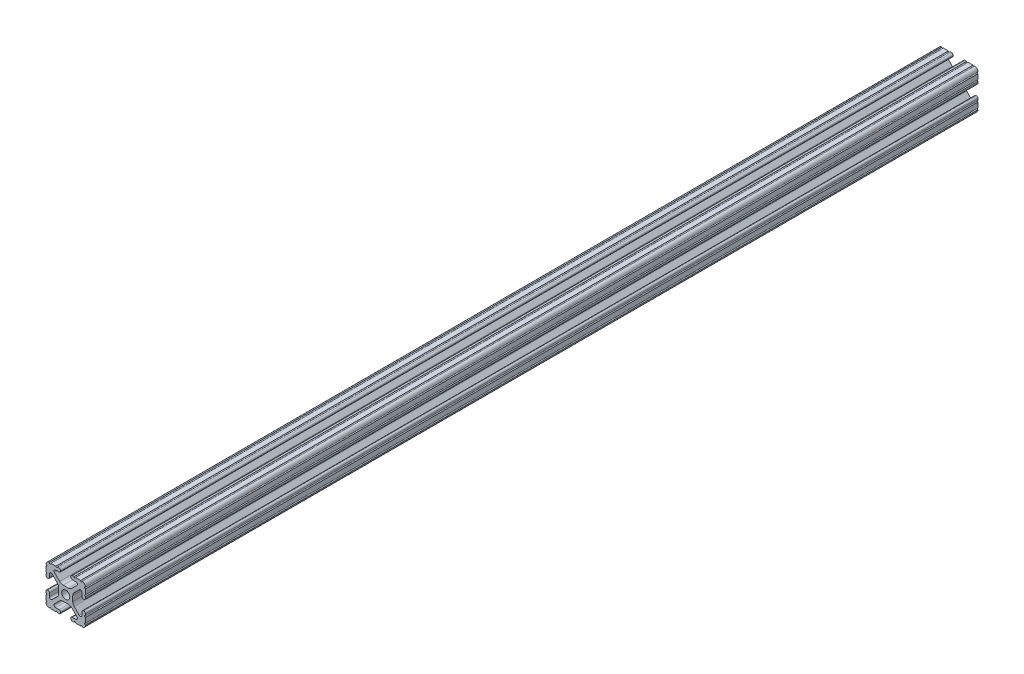
SolidWorks part; units mm, degrees
ref_plane "Front Plane" through (0, 0, 0) normal (0, 0, 1) x (1, 0, 0)
ref_plane "Top Plane" through (0, 0, 0) normal (0, 1, 0) x (1, 0, 0)
ref_plane "Right Plane" through (0, 0, 0) normal (1, 0, 0) x (0, 0, -1)
sketch "Sketch1" plane through (0, 0, 0) normal (0, 0, 1) x (1, 0, 0)
  line L88 (-7.1797, -8.6452) -> (-3.9523, -5.4237)
  line L89 (-1.7093, -4.4958) -> (1.7093, -4.4958)
  line L90 (3.9523, -5.4237) -> (7.1797, -8.6452)
  line L91 (6.4164, -10.4902) -> (4.2875, -10.4902)
  line L92 (3.2385, -11.5392) -> (3.2385, -11.651)
  line L93 (4.2875, -12.7) -> (5.3171, -12.7)
  line L94 (6.3331, -12.7) -> (9.5504, -12.7)
  line L95 (12.7, -9.5504) -> (12.7, -6.3331)
  line L96 (12.7, -5.3171) -> (12.7, -4.2875)
  line L97 (11.651, -3.2385) -> (11.5392, -3.2385)
  line L98 (10.4902, -4.2875) -> (10.4902, -6.4021)
  line L99 (8.7371, -7.1294) -> (5.441, -3.8408)
  line L100 (4.5085, -1.5932) -> (4.5085, 1.5932)
  line L101 (5.441, 3.8408) -> (8.7371, 7.1294)
  line L102 (10.4902, 6.4021) -> (10.4902, 4.2875)
  line L103 (11.5392, 3.2385) -> (11.651, 3.2385)
  line L104 (12.7, 4.2875) -> (12.7, 5.3171)
  line L105 (12.7, 6.3331) -> (12.7, 9.5504)
  line L106 (9.5504, 12.7) -> (6.3331, 12.7)
  line L107 (5.3171, 12.7) -> (4.2875, 12.7)
  line L108 (3.2385, 11.651) -> (3.2385, 11.5392)
  line L109 (4.2875, 10.4902) -> (6.4768, 10.4902)
  line L110 (7.207, 8.7244) -> (3.8983, 5.4232)
  line L111 (1.6558, 4.4958) -> (-1.6558, 4.4958)
  line L112 (-3.8983, 5.4232) -> (-7.207, 8.7244)
  line L113 (-6.4768, 10.4902) -> (-4.2875, 10.4902)
  line L114 (-3.2385, 11.5392) -> (-3.2385, 11.651)
  line L115 (-4.2875, 12.7) -> (-5.3171, 12.7)
  line L116 (-6.3331, 12.7) -> (-9.5504, 12.7)
  line L117 (-12.7, 9.5504) -> (-12.7, 6.3331)
  line L118 (-12.7, 5.3171) -> (-12.7, 4.2875)
  line L119 (-11.651, 3.2385) -> (-11.5392, 3.2385)
  line L120 (-10.4902, 4.2875) -> (-10.4902, 6.4021)
  line L121 (-8.7371, 7.1294) -> (-5.441, 3.8408)
  line L122 (-4.5085, 1.5932) -> (-4.5085, -1.5932)
  line L123 (-5.441, -3.8408) -> (-8.7371, -7.1294)
  line L124 (-10.4902, -6.4021) -> (-10.4902, -4.2875)
  line L125 (-11.5392, -3.2385) -> (-11.651, -3.2385)
  line L126 (-12.7, -4.2875) -> (-12.7, -5.3171)
  line L127 (-12.7, -6.3331) -> (-12.7, -9.5504)
  line L128 (-9.5504, -12.7) -> (-6.3331, -12.7)
  line L129 (-5.3171, -12.7) -> (-4.2875, -12.7)
  line L130 (-3.2385, -11.651) -> (-3.2385, -11.5392)
  line L131 (-4.2875, -10.4902) -> (-6.4164, -10.4902)
  circle A1 centre (0, 0) radius 2.6035
  arc A104 (-7.1797, -8.6452) -> (-6.4164, -10.4902) centre (-6.4164, -9.4098) ccw
  arc A105 (-1.7093, -4.4958) -> (-3.9523, -5.4237) centre (-1.7093, -7.6708) ccw
  arc A106 (3.9523, -5.4237) -> (1.7093, -4.4958) centre (1.7093, -7.6708) ccw
  arc A107 (6.4164, -10.4902) -> (7.1797, -8.6452) centre (6.4164, -9.4098) ccw
  arc A108 (4.2875, -10.4902) -> (3.2385, -11.5392) centre (4.2875, -11.5392) ccw
  arc A109 (3.2385, -11.651) -> (4.2875, -12.7) centre (4.2875, -11.651) ccw
  arc A110 (6.3331, -12.7) -> (5.3171, -12.7) centre (5.8251, -12.7) ccw
  arc A111 (10.5664, -12.6998) -> (9.5504, -12.7) centre (10.0584, -12.7) ccw
  arc A112 (10.5664, -12.6998) -> (12.6998, -10.5664) centre (10.5918, -10.5918) ccw
  arc A113 (12.7, -9.5504) -> (12.6998, -10.5664) centre (12.7, -10.0584) ccw
  arc A114 (12.7, -5.3171) -> (12.7, -6.3331) centre (12.7, -5.8251) ccw
  arc A115 (12.7, -4.2875) -> (11.651, -3.2385) centre (11.651, -4.2875) ccw
  arc A116 (11.5392, -3.2385) -> (10.4902, -4.2875) centre (11.5392, -4.2875) ccw
  arc A117 (8.7371, -7.1294) -> (10.4902, -6.4021) centre (9.4628, -6.4021) ccw
  arc A118 (4.5085, -1.5932) -> (5.441, -3.8408) centre (7.6835, -1.5932) ccw
  arc A119 (5.441, 3.8408) -> (4.5085, 1.5932) centre (7.6835, 1.5932) ccw
  arc A120 (10.4902, 6.4021) -> (8.7371, 7.1294) centre (9.4628, 6.4021) ccw
  arc A121 (10.4902, 4.2875) -> (11.5392, 3.2385) centre (11.5392, 4.2875) ccw
  arc A122 (11.651, 3.2385) -> (12.7, 4.2875) centre (11.651, 4.2875) ccw
  arc A123 (12.7, 6.3331) -> (12.7, 5.3171) centre (12.7, 5.8251) ccw
  arc A124 (12.6998, 10.5664) -> (12.7, 9.5504) centre (12.7, 10.0584) ccw
  arc A125 (12.6998, 10.5664) -> (10.5664, 12.6998) centre (10.5918, 10.5918) ccw
  arc A126 (9.5504, 12.7) -> (10.5664, 12.6998) centre (10.0584, 12.7) ccw
  arc A127 (5.3171, 12.7) -> (6.3331, 12.7) centre (5.8251, 12.7) ccw
  arc A128 (4.2875, 12.7) -> (3.2385, 11.651) centre (4.2875, 11.651) ccw
  arc A129 (3.2385, 11.5392) -> (4.2875, 10.4902) centre (4.2875, 11.5392) ccw
  arc A130 (7.207, 8.7244) -> (6.4768, 10.4902) centre (6.4768, 9.4563) ccw
  arc A131 (1.6558, 4.4958) -> (3.8983, 5.4232) centre (1.6558, 7.6708) ccw
  arc A132 (-3.8983, 5.4232) -> (-1.6558, 4.4958) centre (-1.6558, 7.6708) ccw
  arc A133 (-6.4768, 10.4902) -> (-7.207, 8.7244) centre (-6.4768, 9.4563) ccw
  arc A134 (-4.2875, 10.4902) -> (-3.2385, 11.5392) centre (-4.2875, 11.5392) ccw
  arc A135 (-3.2385, 11.651) -> (-4.2875, 12.7) centre (-4.2875, 11.651) ccw
  arc A136 (-6.3331, 12.7) -> (-5.3171, 12.7) centre (-5.8251, 12.7) ccw
  arc A137 (-10.5664, 12.6998) -> (-9.5504, 12.7) centre (-10.0584, 12.7) ccw
  arc A138 (-10.5664, 12.6998) -> (-12.6998, 10.5664) centre (-10.5918, 10.5918) ccw
  arc A139 (-12.7, 9.5504) -> (-12.6998, 10.5664) centre (-12.7, 10.0584) ccw
  arc A140 (-12.7, 5.3171) -> (-12.7, 6.3331) centre (-12.7, 5.8251) ccw
  arc A141 (-12.7, 4.2875) -> (-11.651, 3.2385) centre (-11.651, 4.2875) ccw
  arc A142 (-11.5392, 3.2385) -> (-10.4902, 4.2875) centre (-11.5392, 4.2875) ccw
  arc A143 (-8.7371, 7.1294) -> (-10.4902, 6.4021) centre (-9.4628, 6.4021) ccw
  arc A144 (-4.5085, 1.5932) -> (-5.441, 3.8408) centre (-7.6835, 1.5932) ccw
  arc A145 (-5.441, -3.8408) -> (-4.5085, -1.5932) centre (-7.6835, -1.5932) ccw
  arc A146 (-10.4902, -6.4021) -> (-8.7371, -7.1294) centre (-9.4628, -6.4021) ccw
  arc A147 (-10.4902, -4.2875) -> (-11.5392, -3.2385) centre (-11.5392, -4.2875) ccw
  arc A148 (-11.651, -3.2385) -> (-12.7, -4.2875) centre (-11.651, -4.2875) ccw
  arc A149 (-12.7, -6.3331) -> (-12.7, -5.3171) centre (-12.7, -5.8251) ccw
  arc A150 (-12.6998, -10.5664) -> (-12.7, -9.5504) centre (-12.7, -10.0584) ccw
  arc A151 (-12.6998, -10.5664) -> (-10.5664, -12.6998) centre (-10.5918, -10.5918) ccw
  arc A152 (-9.5504, -12.7) -> (-10.5664, -12.6998) centre (-10.0584, -12.7) ccw
  arc A153 (-5.3171, -12.7) -> (-6.3331, -12.7) centre (-5.8251, -12.7) ccw
  arc A154 (-4.2875, -12.7) -> (-3.2385, -11.651) centre (-4.2875, -11.651) ccw
  arc A155 (-3.2385, -11.5392) -> (-4.2875, -10.4902) centre (-4.2875, -11.5392) ccw
extrude "Boss-Extrude1" add sketch "Sketch1" along normal mid plane 574.8
sketch "Sketch2" plane through (0, 0, 287.4) normal (0, 0, 1) x (1, 0, 0)
  line L44 (-7.1797, -8.6452) -> (-3.9523, -5.4237)
  line L45 (-1.7093, -4.4958) -> (1.7093, -4.4958)
  line L46 (3.9523, -5.4237) -> (7.1797, -8.6452)
  line L47 (6.4164, -10.4902) -> (4.2875, -10.4902)
  line L48 (3.2385, -11.5392) -> (3.2385, -11.651)
  line L49 (4.2875, -12.7) -> (5.3171, -12.7)
  line L50 (6.3331, -12.7) -> (9.5504, -12.7)
  line L51 (12.7, -9.5504) -> (12.7, -6.3331)
  line L52 (12.7, -5.3171) -> (12.7, -4.2875)
  line L53 (11.651, -3.2385) -> (11.5392, -3.2385)
  line L54 (10.4902, -4.2875) -> (10.4902, -6.4021)
  line L55 (8.7371, -7.1294) -> (5.441, -3.8408)
  line L56 (4.5085, -1.5932) -> (4.5085, 1.5932)
  line L57 (5.441, 3.8408) -> (8.7371, 7.1294)
  line L58 (10.4902, 6.4021) -> (10.4902, 4.2875)
  line L59 (11.5392, 3.2385) -> (11.651, 3.2385)
  line L60 (12.7, 4.2875) -> (12.7, 5.3171)
  line L61 (12.7, 6.3331) -> (12.7, 9.5504)
  line L62 (9.5504, 12.7) -> (6.3331, 12.7)
  line L63 (5.3171, 12.7) -> (4.2875, 12.7)
  line L64 (3.2385, 11.651) -> (3.2385, 11.5392)
  line L65 (4.2875, 10.4902) -> (6.4768, 10.4902)
  line L66 (7.207, 8.7244) -> (3.8983, 5.4232)
  line L67 (1.6558, 4.4958) -> (-1.6558, 4.4958)
  line L68 (-3.8983, 5.4232) -> (-7.207, 8.7244)
  line L69 (-6.4768, 10.4902) -> (-4.2875, 10.4902)
  line L70 (-3.2385, 11.5392) -> (-3.2385, 11.651)
  line L71 (-4.2875, 12.7) -> (-5.3171, 12.7)
  line L72 (-6.3331, 12.7) -> (-9.5504, 12.7)
  line L73 (-12.7, 9.5504) -> (-12.7, 6.3331)
  line L74 (-12.7, 5.3171) -> (-12.7, 4.2875)
  line L75 (-11.651, 3.2385) -> (-11.5392, 3.2385)
  line L76 (-10.4902, 4.2875) -> (-10.4902, 6.4021)
  line L77 (-8.7371, 7.1294) -> (-5.441, 3.8408)
  line L78 (-4.5085, 1.5932) -> (-4.5085, -1.5932)
  line L79 (-5.441, -3.8408) -> (-8.7371, -7.1294)
  line L80 (-10.4902, -6.4021) -> (-10.4902, -4.2875)
  line L81 (-11.5392, -3.2385) -> (-11.651, -3.2385)
  line L82 (-12.7, -4.2875) -> (-12.7, -5.3171)
  line L83 (-12.7, -6.3331) -> (-12.7, -9.5504)
  line L84 (-9.5504, -12.7) -> (-6.3331, -12.7)
  line L85 (-5.3171, -12.7) -> (-4.2875, -12.7)
  line L86 (-3.2385, -11.651) -> (-3.2385, -11.5392)
  line L87 (-4.2875, -10.4902) -> (-6.4164, -10.4902)
  line L88 (-7.1797, -8.6452) -> (-3.9523, -5.4237)
  line L89 (-1.7093, -4.4958) -> (1.7093, -4.4958)
  line L90 (3.9523, -5.4237) -> (7.1797, -8.6452)
  line L91 (6.4164, -10.4902) -> (4.2875, -10.4902)
  line L92 (3.2385, -11.5392) -> (3.2385, -11.651)
  line L93 (4.2875, -12.7) -> (5.3171, -12.7)
  line L94 (6.3331, -12.7) -> (9.5504, -12.7)
  line L95 (12.7, -9.5504) -> (12.7, -6.3331)
  line L96 (12.7, -5.3171) -> (12.7, -4.2875)
  line L97 (11.651, -3.2385) -> (11.5392, -3.2385)
  line L98 (10.4902, -4.2875) -> (10.4902, -6.4021)
  line L99 (8.7371, -7.1294) -> (5.441, -3.8408)
  line L100 (4.5085, -1.5932) -> (4.5085, 1.5932)
  line L101 (5.441, 3.8408) -> (8.7371, 7.1294)
  line L102 (10.4902, 6.4021) -> (10.4902, 4.2875)
  line L103 (11.5392, 3.2385) -> (11.651, 3.2385)
  line L104 (12.7, 4.2875) -> (12.7, 5.3171)
  line L105 (12.7, 6.3331) -> (12.7, 9.5504)
  line L106 (9.5504, 12.7) -> (6.3331, 12.7)
  line L107 (5.3171, 12.7) -> (4.2875, 12.7)
  line L108 (3.2385, 11.651) -> (3.2385, 11.5392)
  line L109 (4.2875, 10.4902) -> (6.4768, 10.4902)
  line L110 (7.207, 8.7244) -> (3.8983, 5.4232)
  line L111 (1.6558, 4.4958) -> (-1.6558, 4.4958)
  line L112 (-3.8983, 5.4232) -> (-7.207, 8.7244)
  line L113 (-6.4768, 10.4902) -> (-4.2875, 10.4902)
  line L114 (-3.2385, 11.5392) -> (-3.2385, 11.651)
  line L115 (-4.2875, 12.7) -> (-5.3171, 12.7)
  line L116 (-6.3331, 12.7) -> (-9.5504, 12.7)
  line L117 (-12.7, 9.5504) -> (-12.7, 6.3331)
  line L118 (-12.7, 5.3171) -> (-12.7, 4.2875)
  line L119 (-11.651, 3.2385) -> (-11.5392, 3.2385)
  line L120 (-10.4902, 4.2875) -> (-10.4902, 6.4021)
  line L121 (-8.7371, 7.1294) -> (-5.441, 3.8408)
  line L122 (-4.5085, 1.5932) -> (-4.5085, -1.5932)
  line L123 (-5.441, -3.8408) -> (-8.7371, -7.1294)
  line L124 (-10.4902, -6.4021) -> (-10.4902, -4.2875)
  line L125 (-11.5392, -3.2385) -> (-11.651, -3.2385)
  line L126 (-12.7, -4.2875) -> (-12.7, -5.3171)
  line L127 (-12.7, -6.3331) -> (-12.7, -9.5504)
  line L128 (-9.5504, -12.7) -> (-6.3331, -12.7)
  line L129 (-5.3171, -12.7) -> (-4.2875, -12.7)
  line L130 (-3.2385, -11.651) -> (-3.2385, -11.5392)
  line L131 (-4.2875, -10.4902) -> (-6.4164, -10.4902)
  circle A0 centre (0, 0) radius 2.6035 construction
  circle A1 centre (0, 0) radius 2.6035
  arc A52 (-7.1797, -8.6452) -> (-6.4164, -10.4902) centre (-6.4164, -9.4098) ccw
  arc A53 (-1.7093, -4.4958) -> (-3.9523, -5.4237) centre (-1.7093, -7.6708) ccw
  arc A54 (3.9523, -5.4237) -> (1.7093, -4.4958) centre (1.7093, -7.6708) ccw
  arc A55 (6.4164, -10.4902) -> (7.1797, -8.6452) centre (6.4164, -9.4098) ccw
  arc A56 (4.2875, -10.4902) -> (3.2385, -11.5392) centre (4.2875, -11.5392) ccw
  arc A57 (3.2385, -11.651) -> (4.2875, -12.7) centre (4.2875, -11.651) ccw
  arc A58 (6.3331, -12.7) -> (5.3171, -12.7) centre (5.8251, -12.7) ccw
  arc A59 (10.5664, -12.6998) -> (9.5504, -12.7) centre (10.0584, -12.7) ccw
  arc A60 (10.5664, -12.6998) -> (12.6998, -10.5664) centre (10.5918, -10.5918) ccw
  arc A61 (12.7, -9.5504) -> (12.6998, -10.5664) centre (12.7, -10.0584) ccw
  arc A62 (12.7, -5.3171) -> (12.7, -6.3331) centre (12.7, -5.8251) ccw
  arc A63 (12.7, -4.2875) -> (11.651, -3.2385) centre (11.651, -4.2875) ccw
  arc A64 (11.5392, -3.2385) -> (10.4902, -4.2875) centre (11.5392, -4.2875) ccw
  arc A65 (8.7371, -7.1294) -> (10.4902, -6.4021) centre (9.4628, -6.4021) ccw
  arc A66 (4.5085, -1.5932) -> (5.441, -3.8408) centre (7.6835, -1.5932) ccw
  arc A67 (5.441, 3.8408) -> (4.5085, 1.5932) centre (7.6835, 1.5932) ccw
  arc A68 (10.4902, 6.4021) -> (8.7371, 7.1294) centre (9.4628, 6.4021) ccw
  arc A69 (10.4902, 4.2875) -> (11.5392, 3.2385) centre (11.5392, 4.2875) ccw
  arc A70 (11.651, 3.2385) -> (12.7, 4.2875) centre (11.651, 4.2875) ccw
  arc A71 (12.7, 6.3331) -> (12.7, 5.3171) centre (12.7, 5.8251) ccw
  arc A72 (12.6998, 10.5664) -> (12.7, 9.5504) centre (12.7, 10.0584) ccw
  arc A73 (12.6998, 10.5664) -> (10.5664, 12.6998) centre (10.5918, 10.5918) ccw
  arc A74 (9.5504, 12.7) -> (10.5664, 12.6998) centre (10.0584, 12.7) ccw
  arc A75 (5.3171, 12.7) -> (6.3331, 12.7) centre (5.8251, 12.7) ccw
  arc A76 (4.2875, 12.7) -> (3.2385, 11.651) centre (4.2875, 11.651) ccw
  arc A77 (3.2385, 11.5392) -> (4.2875, 10.4902) centre (4.2875, 11.5392) ccw
  arc A78 (7.207, 8.7244) -> (6.4768, 10.4902) centre (6.4768, 9.4563) ccw
  arc A79 (1.6558, 4.4958) -> (3.8983, 5.4232) centre (1.6558, 7.6708) ccw
  arc A80 (-3.8983, 5.4232) -> (-1.6558, 4.4958) centre (-1.6558, 7.6708) ccw
  arc A81 (-6.4768, 10.4902) -> (-7.207, 8.7244) centre (-6.4768, 9.4563) ccw
  arc A82 (-4.2875, 10.4902) -> (-3.2385, 11.5392) centre (-4.2875, 11.5392) ccw
  arc A83 (-3.2385, 11.651) -> (-4.2875, 12.7) centre (-4.2875, 11.651) ccw
  arc A84 (-6.3331, 12.7) -> (-5.3171, 12.7) centre (-5.8251, 12.7) ccw
  arc A85 (-10.5664, 12.6998) -> (-9.5504, 12.7) centre (-10.0584, 12.7) ccw
  arc A86 (-10.5664, 12.6998) -> (-12.6998, 10.5664) centre (-10.5918, 10.5918) ccw
  arc A87 (-12.7, 9.5504) -> (-12.6998, 10.5664) centre (-12.7, 10.0584) ccw
  arc A88 (-12.7, 5.3171) -> (-12.7, 6.3331) centre (-12.7, 5.8251) ccw
  arc A89 (-12.7, 4.2875) -> (-11.651, 3.2385) centre (-11.651, 4.2875) ccw
  arc A90 (-11.5392, 3.2385) -> (-10.4902, 4.2875) centre (-11.5392, 4.2875) ccw
  arc A91 (-8.7371, 7.1294) -> (-10.4902, 6.4021) centre (-9.4628, 6.4021) ccw
  arc A92 (-4.5085, 1.5932) -> (-5.441, 3.8408) centre (-7.6835, 1.5932) ccw
  arc A93 (-5.441, -3.8408) -> (-4.5085, -1.5932) centre (-7.6835, -1.5932) ccw
  arc A94 (-10.4902, -6.4021) -> (-8.7371, -7.1294) centre (-9.4628, -6.4021) ccw
  arc A95 (-10.4902, -4.2875) -> (-11.5392, -3.2385) centre (-11.5392, -4.2875) ccw
  arc A96 (-11.651, -3.2385) -> (-12.7, -4.2875) centre (-11.651, -4.2875) ccw
  arc A97 (-12.7, -6.3331) -> (-12.7, -5.3171) centre (-12.7, -5.8251) ccw
  arc A98 (-12.6998, -10.5664) -> (-12.7, -9.5504) centre (-12.7, -10.0584) ccw
  arc A99 (-12.6998, -10.5664) -> (-10.5664, -12.6998) centre (-10.5918, -10.5918) ccw
  arc A100 (-9.5504, -12.7) -> (-10.5664, -12.6998) centre (-10.0584, -12.7) ccw
  arc A101 (-5.3171, -12.7) -> (-6.3331, -12.7) centre (-5.8251, -12.7) ccw
  arc A102 (-4.2875, -12.7) -> (-3.2385, -11.651) centre (-4.2875, -11.651) ccw
  arc A103 (-3.2385, -11.5392) -> (-4.2875, -10.4902) centre (-4.2875, -11.5392) ccw
  arc A104 (-7.1797, -8.6452) -> (-6.4164, -10.4902) centre (-6.4164, -9.4098) ccw
  arc A105 (-1.7093, -4.4958) -> (-3.9523, -5.4237) centre (-1.7093, -7.6708) ccw
  arc A106 (3.9523, -5.4237) -> (1.7093, -4.4958) centre (1.7093, -7.6708) ccw
  arc A107 (6.4164, -10.4902) -> (7.1797, -8.6452) centre (6.4164, -9.4098) ccw
  arc A108 (4.2875, -10.4902) -> (3.2385, -11.5392) centre (4.2875, -11.5392) ccw
  arc A109 (3.2385, -11.651) -> (4.2875, -12.7) centre (4.2875, -11.651) ccw
  arc A110 (6.3331, -12.7) -> (5.3171, -12.7) centre (5.8251, -12.7) ccw
  arc A111 (10.5664, -12.6998) -> (9.5504, -12.7) centre (10.0584, -12.7) ccw
  arc A112 (10.5664, -12.6998) -> (12.6998, -10.5664) centre (10.5918, -10.5918) ccw
  arc A113 (12.7, -9.5504) -> (12.6998, -10.5664) centre (12.7, -10.0584) ccw
  arc A114 (12.7, -5.3171) -> (12.7, -6.3331) centre (12.7, -5.8251) ccw
  arc A115 (12.7, -4.2875) -> (11.651, -3.2385) centre (11.651, -4.2875) ccw
  arc A116 (11.5392, -3.2385) -> (10.4902, -4.2875) centre (11.5392, -4.2875) ccw
  arc A117 (8.7371, -7.1294) -> (10.4902, -6.4021) centre (9.4628, -6.4021) ccw
  arc A118 (4.5085, -1.5932) -> (5.441, -3.8408) centre (7.6835, -1.5932) ccw
  arc A119 (5.441, 3.8408) -> (4.5085, 1.5932) centre (7.6835, 1.5932) ccw
  arc A120 (10.4902, 6.4021) -> (8.7371, 7.1294) centre (9.4628, 6.4021) ccw
  arc A121 (10.4902, 4.2875) -> (11.5392, 3.2385) centre (11.5392, 4.2875) ccw
  arc A122 (11.651, 3.2385) -> (12.7, 4.2875) centre (11.651, 4.2875) ccw
  arc A123 (12.7, 6.3331) -> (12.7, 5.3171) centre (12.7, 5.8251) ccw
  arc A124 (12.6998, 10.5664) -> (12.7, 9.5504) centre (12.7, 10.0584) ccw
  arc A125 (12.6998, 10.5664) -> (10.5664, 12.6998) centre (10.5918, 10.5918) ccw
  arc A126 (9.5504, 12.7) -> (10.5664, 12.6998) centre (10.0584, 12.7) ccw
  arc A127 (5.3171, 12.7) -> (6.3331, 12.7) centre (5.8251, 12.7) ccw
  arc A128 (4.2875, 12.7) -> (3.2385, 11.651) centre (4.2875, 11.651) ccw
  arc A129 (3.2385, 11.5392) -> (4.2875, 10.4902) centre (4.2875, 11.5392) ccw
  arc A130 (7.207, 8.7244) -> (6.4768, 10.4902) centre (6.4768, 9.4563) ccw
  arc A131 (1.6558, 4.4958) -> (3.8983, 5.4232) centre (1.6558, 7.6708) ccw
  arc A132 (-3.8983, 5.4232) -> (-1.6558, 4.4958) centre (-1.6558, 7.6708) ccw
  arc A133 (-6.4768, 10.4902) -> (-7.207, 8.7244) centre (-6.4768, 9.4563) ccw
  arc A134 (-4.2875, 10.4902) -> (-3.2385, 11.5392) centre (-4.2875, 11.5392) ccw
  arc A135 (-3.2385, 11.651) -> (-4.2875, 12.7) centre (-4.2875, 11.651) ccw
  arc A136 (-6.3331, 12.7) -> (-5.3171, 12.7) centre (-5.8251, 12.7) ccw
  arc A137 (-10.5664, 12.6998) -> (-9.5504, 12.7) centre (-10.0584, 12.7) ccw
  arc A138 (-10.5664, 12.6998) -> (-12.6998, 10.5664) centre (-10.5918, 10.5918) ccw
  arc A139 (-12.7, 9.5504) -> (-12.6998, 10.5664) centre (-12.7, 10.0584) ccw
  arc A140 (-12.7, 5.3171) -> (-12.7, 6.3331) centre (-12.7, 5.8251) ccw
  arc A141 (-12.7, 4.2875) -> (-11.651, 3.2385) centre (-11.651, 4.2875) ccw
  arc A142 (-11.5392, 3.2385) -> (-10.4902, 4.2875) centre (-11.5392, 4.2875) ccw
  arc A143 (-8.7371, 7.1294) -> (-10.4902, 6.4021) centre (-9.4628, 6.4021) ccw
  arc A144 (-4.5085, 1.5932) -> (-5.441, 3.8408) centre (-7.6835, 1.5932) ccw
  arc A145 (-5.441, -3.8408) -> (-4.5085, -1.5932) centre (-7.6835, -1.5932) ccw
  arc A146 (-10.4902, -6.4021) -> (-8.7371, -7.1294) centre (-9.4628, -6.4021) ccw
  arc A147 (-10.4902, -4.2875) -> (-11.5392, -3.2385) centre (-11.5392, -4.2875) ccw
  arc A148 (-11.651, -3.2385) -> (-12.7, -4.2875) centre (-11.651, -4.2875) ccw
  arc A149 (-12.7, -6.3331) -> (-12.7, -5.3171) centre (-12.7, -5.8251) ccw
  arc A150 (-12.6998, -10.5664) -> (-12.7, -9.5504) centre (-12.7, -10.0584) ccw
  arc A151 (-12.6998, -10.5664) -> (-10.5664, -12.6998) centre (-10.5918, -10.5918) ccw
  arc A152 (-9.5504, -12.7) -> (-10.5664, -12.6998) centre (-10.0584, -12.7) ccw
  arc A153 (-5.3171, -12.7) -> (-6.3331, -12.7) centre (-5.8251, -12.7) ccw
  arc A154 (-4.2875, -12.7) -> (-3.2385, -11.651) centre (-4.2875, -11.651) ccw
  arc A155 (-3.2385, -11.5392) -> (-4.2875, -10.4902) centre (-4.2875, -11.5392) ccw
  dimension "D1" = 0
extrude "Boss-Extrude2" [suppressed] add sketch "Sketch2" against normal blind 1300
sketch "Sketch8" plane through (0, 0, 287.4) normal (0, 0, 1) x (1, 0, 0)
  line L44 (-7.1797, -8.6452) -> (-3.9523, -5.4237)
  line L45 (-1.7093, -4.4958) -> (1.7093, -4.4958)
  line L46 (3.9523, -5.4237) -> (7.1797, -8.6452)
  line L47 (6.4164, -10.4902) -> (4.2875, -10.4902)
  line L48 (3.2385, -11.5392) -> (3.2385, -11.651)
  line L49 (4.2875, -12.7) -> (5.3171, -12.7)
  line L50 (6.3331, -12.7) -> (9.5504, -12.7)
  line L51 (12.7, -9.5504) -> (12.7, -6.3331)
  line L52 (12.7, -5.3171) -> (12.7, -4.2875)
  line L53 (11.651, -3.2385) -> (11.5392, -3.2385)
  line L54 (10.4902, -4.2875) -> (10.4902, -6.4021)
  line L55 (8.7371, -7.1294) -> (5.441, -3.8408)
  line L56 (4.5085, -1.5932) -> (4.5085, 1.5932)
  line L57 (5.441, 3.8408) -> (8.7371, 7.1294)
  line L58 (10.4902, 6.4021) -> (10.4902, 4.2875)
  line L59 (11.5392, 3.2385) -> (11.651, 3.2385)
  line L60 (12.7, 4.2875) -> (12.7, 5.3171)
  line L61 (12.7, 6.3331) -> (12.7, 9.5504)
  line L62 (9.5504, 12.7) -> (6.3331, 12.7)
  line L63 (5.3171, 12.7) -> (4.2875, 12.7)
  line L64 (3.2385, 11.651) -> (3.2385, 11.5392)
  line L65 (4.2875, 10.4902) -> (6.4768, 10.4902)
  line L66 (7.207, 8.7244) -> (3.8983, 5.4232)
  line L67 (1.6558, 4.4958) -> (-1.6558, 4.4958)
  line L68 (-3.8983, 5.4232) -> (-7.207, 8.7244)
  line L69 (-6.4768, 10.4902) -> (-4.2875, 10.4902)
  line L70 (-3.2385, 11.5392) -> (-3.2385, 11.651)
  line L71 (-4.2875, 12.7) -> (-5.3171, 12.7)
  line L72 (-6.3331, 12.7) -> (-9.5504, 12.7)
  line L73 (-12.7, 9.5504) -> (-12.7, 6.3331)
  line L74 (-12.7, 5.3171) -> (-12.7, 4.2875)
  line L75 (-11.651, 3.2385) -> (-11.5392, 3.2385)
  line L76 (-10.4902, 4.2875) -> (-10.4902, 6.4021)
  line L77 (-8.7371, 7.1294) -> (-5.441, 3.8408)
  line L78 (-4.5085, 1.5932) -> (-4.5085, -1.5932)
  line L79 (-5.441, -3.8408) -> (-8.7371, -7.1294)
  line L80 (-10.4902, -6.4021) -> (-10.4902, -4.2875)
  line L81 (-11.5392, -3.2385) -> (-11.651, -3.2385)
  line L82 (-12.7, -4.2875) -> (-12.7, -5.3171)
  line L83 (-12.7, -6.3331) -> (-12.7, -9.5504)
  line L84 (-9.5504, -12.7) -> (-6.3331, -12.7)
  line L85 (-5.3171, -12.7) -> (-4.2875, -12.7)
  line L86 (-3.2385, -11.651) -> (-3.2385, -11.5392)
  line L87 (-4.2875, -10.4902) -> (-6.4164, -10.4902)
  line L88 (-7.1797, -8.6452) -> (-3.9523, -5.4237)
  line L89 (-1.7093, -4.4958) -> (1.7093, -4.4958)
  line L90 (3.9523, -5.4237) -> (7.1797, -8.6452)
  line L91 (6.4164, -10.4902) -> (4.2875, -10.4902)
  line L92 (3.2385, -11.5392) -> (3.2385, -11.651)
  line L93 (4.2875, -12.7) -> (5.3171, -12.7)
  line L94 (6.3331, -12.7) -> (9.5504, -12.7)
  line L95 (12.7, -9.5504) -> (12.7, -6.3331)
  line L96 (12.7, -5.3171) -> (12.7, -4.2875)
  line L97 (11.651, -3.2385) -> (11.5392, -3.2385)
  line L98 (10.4902, -4.2875) -> (10.4902, -6.4021)
  line L99 (8.7371, -7.1294) -> (5.441, -3.8408)
  line L100 (4.5085, -1.5932) -> (4.5085, 1.5932)
  line L101 (5.441, 3.8408) -> (8.7371, 7.1294)
  line L102 (10.4902, 6.4021) -> (10.4902, 4.2875)
  line L103 (11.5392, 3.2385) -> (11.651, 3.2385)
  line L104 (12.7, 4.2875) -> (12.7, 5.3171)
  line L105 (12.7, 6.3331) -> (12.7, 9.5504)
  line L106 (9.5504, 12.7) -> (6.3331, 12.7)
  line L107 (5.3171, 12.7) -> (4.2875, 12.7)
  line L108 (3.2385, 11.651) -> (3.2385, 11.5392)
  line L109 (4.2875, 10.4902) -> (6.4768, 10.4902)
  line L110 (7.207, 8.7244) -> (3.8983, 5.4232)
  line L111 (1.6558, 4.4958) -> (-1.6558, 4.4958)
  line L112 (-3.8983, 5.4232) -> (-7.207, 8.7244)
  line L113 (-6.4768, 10.4902) -> (-4.2875, 10.4902)
  line L114 (-3.2385, 11.5392) -> (-3.2385, 11.651)
  line L115 (-4.2875, 12.7) -> (-5.3171, 12.7)
  line L116 (-6.3331, 12.7) -> (-9.5504, 12.7)
  line L117 (-12.7, 9.5504) -> (-12.7, 6.3331)
  line L118 (-12.7, 5.3171) -> (-12.7, 4.2875)
  line L119 (-11.651, 3.2385) -> (-11.5392, 3.2385)
  line L120 (-10.4902, 4.2875) -> (-10.4902, 6.4021)
  line L121 (-8.7371, 7.1294) -> (-5.441, 3.8408)
  line L122 (-4.5085, 1.5932) -> (-4.5085, -1.5932)
  line L123 (-5.441, -3.8408) -> (-8.7371, -7.1294)
  line L124 (-10.4902, -6.4021) -> (-10.4902, -4.2875)
  line L125 (-11.5392, -3.2385) -> (-11.651, -3.2385)
  line L126 (-12.7, -4.2875) -> (-12.7, -5.3171)
  line L127 (-12.7, -6.3331) -> (-12.7, -9.5504)
  line L128 (-9.5504, -12.7) -> (-6.3331, -12.7)
  line L129 (-5.3171, -12.7) -> (-4.2875, -12.7)
  line L130 (-3.2385, -11.651) -> (-3.2385, -11.5392)
  line L131 (-4.2875, -10.4902) -> (-6.4164, -10.4902)
  circle A0 centre (0, 0) radius 2.6035 construction
  circle A1 centre (0, 0) radius 2.6035
  arc A52 (-7.1797, -8.6452) -> (-6.4164, -10.4902) centre (-6.4164, -9.4098) ccw
  arc A53 (-1.7093, -4.4958) -> (-3.9523, -5.4237) centre (-1.7093, -7.6708) ccw
  arc A54 (3.9523, -5.4237) -> (1.7093, -4.4958) centre (1.7093, -7.6708) ccw
  arc A55 (6.4164, -10.4902) -> (7.1797, -8.6452) centre (6.4164, -9.4098) ccw
  arc A56 (4.2875, -10.4902) -> (3.2385, -11.5392) centre (4.2875, -11.5392) ccw
  arc A57 (3.2385, -11.651) -> (4.2875, -12.7) centre (4.2875, -11.651) ccw
  arc A58 (6.3331, -12.7) -> (5.3171, -12.7) centre (5.8251, -12.7) ccw
  arc A59 (10.5664, -12.6998) -> (9.5504, -12.7) centre (10.0584, -12.7) ccw
  arc A60 (10.5664, -12.6998) -> (12.6998, -10.5664) centre (10.5918, -10.5918) ccw
  arc A61 (12.7, -9.5504) -> (12.6998, -10.5664) centre (12.7, -10.0584) ccw
  arc A62 (12.7, -5.3171) -> (12.7, -6.3331) centre (12.7, -5.8251) ccw
  arc A63 (12.7, -4.2875) -> (11.651, -3.2385) centre (11.651, -4.2875) ccw
  arc A64 (11.5392, -3.2385) -> (10.4902, -4.2875) centre (11.5392, -4.2875) ccw
  arc A65 (8.7371, -7.1294) -> (10.4902, -6.4021) centre (9.4628, -6.4021) ccw
  arc A66 (4.5085, -1.5932) -> (5.441, -3.8408) centre (7.6835, -1.5932) ccw
  arc A67 (5.441, 3.8408) -> (4.5085, 1.5932) centre (7.6835, 1.5932) ccw
  arc A68 (10.4902, 6.4021) -> (8.7371, 7.1294) centre (9.4628, 6.4021) ccw
  arc A69 (10.4902, 4.2875) -> (11.5392, 3.2385) centre (11.5392, 4.2875) ccw
  arc A70 (11.651, 3.2385) -> (12.7, 4.2875) centre (11.651, 4.2875) ccw
  arc A71 (12.7, 6.3331) -> (12.7, 5.3171) centre (12.7, 5.8251) ccw
  arc A72 (12.6998, 10.5664) -> (12.7, 9.5504) centre (12.7, 10.0584) ccw
  arc A73 (12.6998, 10.5664) -> (10.5664, 12.6998) centre (10.5918, 10.5918) ccw
  arc A74 (9.5504, 12.7) -> (10.5664, 12.6998) centre (10.0584, 12.7) ccw
  arc A75 (5.3171, 12.7) -> (6.3331, 12.7) centre (5.8251, 12.7) ccw
  arc A76 (4.2875, 12.7) -> (3.2385, 11.651) centre (4.2875, 11.651) ccw
  arc A77 (3.2385, 11.5392) -> (4.2875, 10.4902) centre (4.2875, 11.5392) ccw
  arc A78 (7.207, 8.7244) -> (6.4768, 10.4902) centre (6.4768, 9.4563) ccw
  arc A79 (1.6558, 4.4958) -> (3.8983, 5.4232) centre (1.6558, 7.6708) ccw
  arc A80 (-3.8983, 5.4232) -> (-1.6558, 4.4958) centre (-1.6558, 7.6708) ccw
  arc A81 (-6.4768, 10.4902) -> (-7.207, 8.7244) centre (-6.4768, 9.4563) ccw
  arc A82 (-4.2875, 10.4902) -> (-3.2385, 11.5392) centre (-4.2875, 11.5392) ccw
  arc A83 (-3.2385, 11.651) -> (-4.2875, 12.7) centre (-4.2875, 11.651) ccw
  arc A84 (-6.3331, 12.7) -> (-5.3171, 12.7) centre (-5.8251, 12.7) ccw
  arc A85 (-10.5664, 12.6998) -> (-9.5504, 12.7) centre (-10.0584, 12.7) ccw
  arc A86 (-10.5664, 12.6998) -> (-12.6998, 10.5664) centre (-10.5918, 10.5918) ccw
  arc A87 (-12.7, 9.5504) -> (-12.6998, 10.5664) centre (-12.7, 10.0584) ccw
  arc A88 (-12.7, 5.3171) -> (-12.7, 6.3331) centre (-12.7, 5.8251) ccw
  arc A89 (-12.7, 4.2875) -> (-11.651, 3.2385) centre (-11.651, 4.2875) ccw
  arc A90 (-11.5392, 3.2385) -> (-10.4902, 4.2875) centre (-11.5392, 4.2875) ccw
  arc A91 (-8.7371, 7.1294) -> (-10.4902, 6.4021) centre (-9.4628, 6.4021) ccw
  arc A92 (-4.5085, 1.5932) -> (-5.441, 3.8408) centre (-7.6835, 1.5932) ccw
  arc A93 (-5.441, -3.8408) -> (-4.5085, -1.5932) centre (-7.6835, -1.5932) ccw
  arc A94 (-10.4902, -6.4021) -> (-8.7371, -7.1294) centre (-9.4628, -6.4021) ccw
  arc A95 (-10.4902, -4.2875) -> (-11.5392, -3.2385) centre (-11.5392, -4.2875) ccw
  arc A96 (-11.651, -3.2385) -> (-12.7, -4.2875) centre (-11.651, -4.2875) ccw
  arc A97 (-12.7, -6.3331) -> (-12.7, -5.3171) centre (-12.7, -5.8251) ccw
  arc A98 (-12.6998, -10.5664) -> (-12.7, -9.5504) centre (-12.7, -10.0584) ccw
  arc A99 (-12.6998, -10.5664) -> (-10.5664, -12.6998) centre (-10.5918, -10.5918) ccw
  arc A100 (-9.5504, -12.7) -> (-10.5664, -12.6998) centre (-10.0584, -12.7) ccw
  arc A101 (-5.3171, -12.7) -> (-6.3331, -12.7) centre (-5.8251, -12.7) ccw
  arc A102 (-4.2875, -12.7) -> (-3.2385, -11.651) centre (-4.2875, -11.651) ccw
  arc A103 (-3.2385, -11.5392) -> (-4.2875, -10.4902) centre (-4.2875, -11.5392) ccw
  arc A104 (-7.1797, -8.6452) -> (-6.4164, -10.4902) centre (-6.4164, -9.4098) ccw
  arc A105 (-1.7093, -4.4958) -> (-3.9523, -5.4237) centre (-1.7093, -7.6708) ccw
  arc A106 (3.9523, -5.4237) -> (1.7093, -4.4958) centre (1.7093, -7.6708) ccw
  arc A107 (6.4164, -10.4902) -> (7.1797, -8.6452) centre (6.4164, -9.4098) ccw
  arc A108 (4.2875, -10.4902) -> (3.2385, -11.5392) centre (4.2875, -11.5392) ccw
  arc A109 (3.2385, -11.651) -> (4.2875, -12.7) centre (4.2875, -11.651) ccw
  arc A110 (6.3331, -12.7) -> (5.3171, -12.7) centre (5.8251, -12.7) ccw
  arc A111 (10.5664, -12.6998) -> (9.5504, -12.7) centre (10.0584, -12.7) ccw
  arc A112 (10.5664, -12.6998) -> (12.6998, -10.5664) centre (10.5918, -10.5918) ccw
  arc A113 (12.7, -9.5504) -> (12.6998, -10.5664) centre (12.7, -10.0584) ccw
  arc A114 (12.7, -5.3171) -> (12.7, -6.3331) centre (12.7, -5.8251) ccw
  arc A115 (12.7, -4.2875) -> (11.651, -3.2385) centre (11.651, -4.2875) ccw
  arc A116 (11.5392, -3.2385) -> (10.4902, -4.2875) centre (11.5392, -4.2875) ccw
  arc A117 (8.7371, -7.1294) -> (10.4902, -6.4021) centre (9.4628, -6.4021) ccw
  arc A118 (4.5085, -1.5932) -> (5.441, -3.8408) centre (7.6835, -1.5932) ccw
  arc A119 (5.441, 3.8408) -> (4.5085, 1.5932) centre (7.6835, 1.5932) ccw
  arc A120 (10.4902, 6.4021) -> (8.7371, 7.1294) centre (9.4628, 6.4021) ccw
  arc A121 (10.4902, 4.2875) -> (11.5392, 3.2385) centre (11.5392, 4.2875) ccw
  arc A122 (11.651, 3.2385) -> (12.7, 4.2875) centre (11.651, 4.2875) ccw
  arc A123 (12.7, 6.3331) -> (12.7, 5.3171) centre (12.7, 5.8251) ccw
  arc A124 (12.6998, 10.5664) -> (12.7, 9.5504) centre (12.7, 10.0584) ccw
  arc A125 (12.6998, 10.5664) -> (10.5664, 12.6998) centre (10.5918, 10.5918) ccw
  arc A126 (9.5504, 12.7) -> (10.5664, 12.6998) centre (10.0584, 12.7) ccw
  arc A127 (5.3171, 12.7) -> (6.3331, 12.7) centre (5.8251, 12.7) ccw
  arc A128 (4.2875, 12.7) -> (3.2385, 11.651) centre (4.2875, 11.651) ccw
  arc A129 (3.2385, 11.5392) -> (4.2875, 10.4902) centre (4.2875, 11.5392) ccw
  arc A130 (7.207, 8.7244) -> (6.4768, 10.4902) centre (6.4768, 9.4563) ccw
  arc A131 (1.6558, 4.4958) -> (3.8983, 5.4232) centre (1.6558, 7.6708) ccw
  arc A132 (-3.8983, 5.4232) -> (-1.6558, 4.4958) centre (-1.6558, 7.6708) ccw
  arc A133 (-6.4768, 10.4902) -> (-7.207, 8.7244) centre (-6.4768, 9.4563) ccw
  arc A134 (-4.2875, 10.4902) -> (-3.2385, 11.5392) centre (-4.2875, 11.5392) ccw
  arc A135 (-3.2385, 11.651) -> (-4.2875, 12.7) centre (-4.2875, 11.651) ccw
  arc A136 (-6.3331, 12.7) -> (-5.3171, 12.7) centre (-5.8251, 12.7) ccw
  arc A137 (-10.5664, 12.6998) -> (-9.5504, 12.7) centre (-10.0584, 12.7) ccw
  arc A138 (-10.5664, 12.6998) -> (-12.6998, 10.5664) centre (-10.5918, 10.5918) ccw
  arc A139 (-12.7, 9.5504) -> (-12.6998, 10.5664) centre (-12.7, 10.0584) ccw
  arc A140 (-12.7, 5.3171) -> (-12.7, 6.3331) centre (-12.7, 5.8251) ccw
  arc A141 (-12.7, 4.2875) -> (-11.651, 3.2385) centre (-11.651, 4.2875) ccw
  arc A142 (-11.5392, 3.2385) -> (-10.4902, 4.2875) centre (-11.5392, 4.2875) ccw
  arc A143 (-8.7371, 7.1294) -> (-10.4902, 6.4021) centre (-9.4628, 6.4021) ccw
  arc A144 (-4.5085, 1.5932) -> (-5.441, 3.8408) centre (-7.6835, 1.5932) ccw
  arc A145 (-5.441, -3.8408) -> (-4.5085, -1.5932) centre (-7.6835, -1.5932) ccw
  arc A146 (-10.4902, -6.4021) -> (-8.7371, -7.1294) centre (-9.4628, -6.4021) ccw
  arc A147 (-10.4902, -4.2875) -> (-11.5392, -3.2385) centre (-11.5392, -4.2875) ccw
  arc A148 (-11.651, -3.2385) -> (-12.7, -4.2875) centre (-11.651, -4.2875) ccw
  arc A149 (-12.7, -6.3331) -> (-12.7, -5.3171) centre (-12.7, -5.8251) ccw
  arc A150 (-12.6998, -10.5664) -> (-12.7, -9.5504) centre (-12.7, -10.0584) ccw
  arc A151 (-12.6998, -10.5664) -> (-10.5664, -12.6998) centre (-10.5918, -10.5918) ccw
  arc A152 (-9.5504, -12.7) -> (-10.5664, -12.6998) centre (-10.0584, -12.7) ccw
  arc A153 (-5.3171, -12.7) -> (-6.3331, -12.7) centre (-5.8251, -12.7) ccw
  arc A154 (-4.2875, -12.7) -> (-3.2385, -11.651) centre (-4.2875, -11.651) ccw
  arc A155 (-3.2385, -11.5392) -> (-4.2875, -10.4902) centre (-4.2875, -11.5392) ccw
  dimension "D1" = 0
extrude "Cut-Extrude6" [suppressed] cut sketch "Sketch8" against normal blind 958
sketch "Sketch10" plane through (0, 0, 0) normal (0, 1, 0) x (1, 0, 0)
  line L0 (-7.4968, -287.4) -> (-6.4164, -287.4) construction
  line L1 (250, 212.6) -> (-250, 212.6)
  line L2 (250, 212.6) -> (250, -287.4)
  line L3 (250, -287.4) -> (-250, -287.4)
  line L4 (-250, 212.6) -> (-250, -287.4)
  line L5 (0, 0) -> (0, -681.6536) construction
  dimension "D1" = 500
  dimension "D2" = 500
extrude "500mm" [suppressed] cut sketch "Sketch10" against normal through all both and the other way through all flip side to cut
